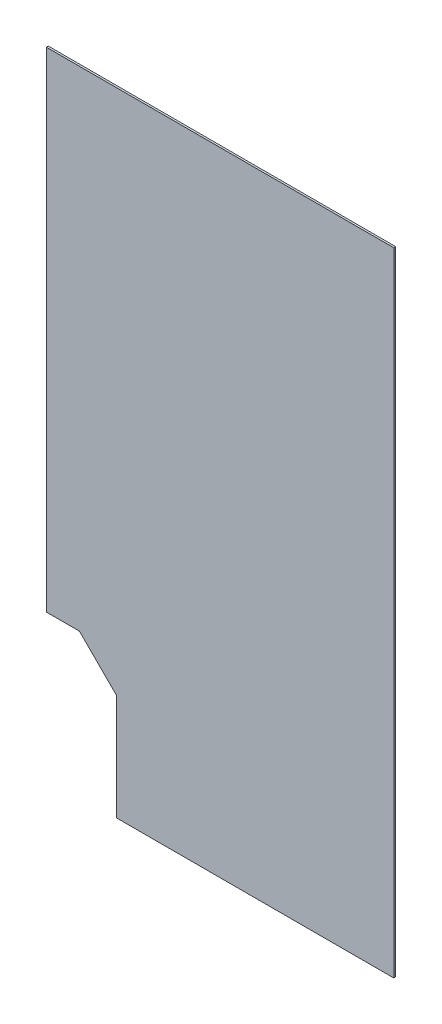
SolidWorks part; units mm, degrees
ref_plane "Front Plane" through (0, 0, 0) normal (0, 0, 1) x (1, 0, 0)
ref_plane "Top Plane" through (0, 0, 0) normal (0, 1, 0) x (1, 0, 0)
ref_plane "Right Plane" through (0, 0, 0) normal (1, 0, 0) x (0, 0, -1)
sketch "Sketch2" plane through (0, 0, 0) normal (0, 0, 1) x (1, 0, 0)
  line L0 (-473.8112, 1472.7692) -> (941.1888, 1472.7692)
  line L1 (941.1888, 1472.7692) -> (941.1888, -1102.2308)
  line L2 (941.1888, -1102.2308) -> (-188.8112, -1102.2308)
  line L3 (-188.8112, -1102.2308) -> (-188.8112, -669.2308)
  line L4 (-188.8112, -669.2308) -> (-338.8112, -519.2308)
  line L5 (-338.8112, -519.2308) -> (-473.8112, -519.2308)
  line L6 (-473.8112, -519.2308) -> (-473.8112, 1472.7692)
  dimension "D1" = 1415
  dimension "D2" = 2575
  dimension "D3" = 150
  dimension "D4" = 135
  dimension "D5" = 150
  dimension "D6" = 1130
  dimension "D7" = 1992
  dimension "D8" = 433
extrude "Boss-Extrude2" add sketch "Sketch2" along normal blind 8
